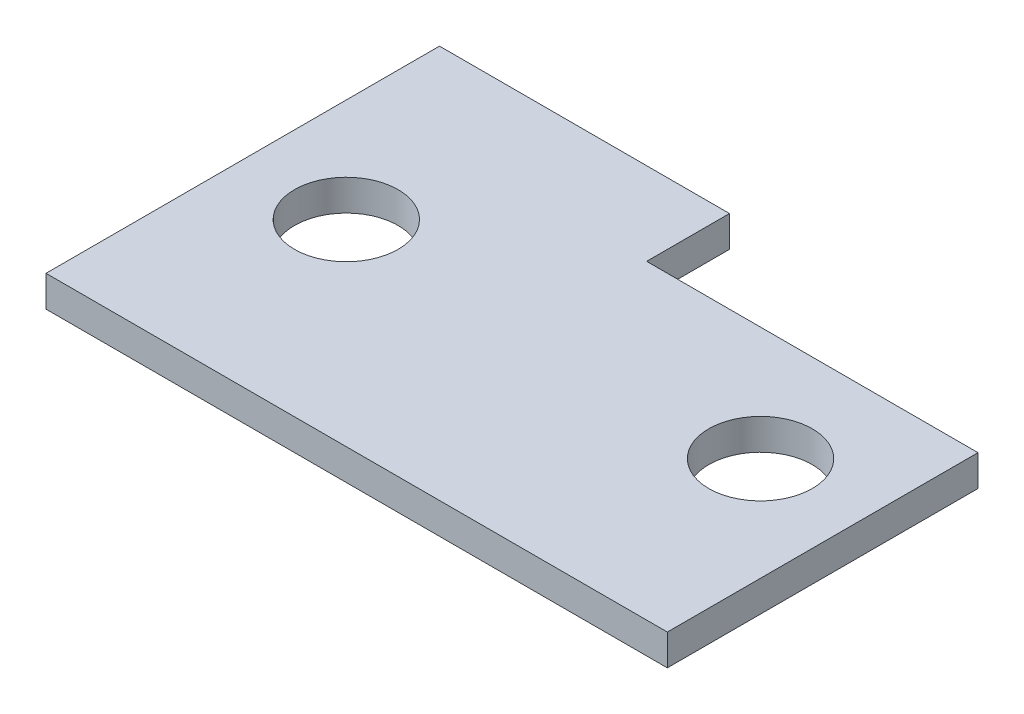
SolidWorks part; units mm, degrees
material "AISI 1020"
ref_plane "Спереди" through (0, 0, 0) normal (0, 0, 1) x (1, 0, 0)
ref_plane "Сверху" through (0, 0, 0) normal (0, 1, 0) x (1, 0, 0)
ref_plane "Справа" through (0, 0, 0) normal (1, 0, 0) x (0, 0, -1)
sketch "Эскиз1" plane through (0, 0, 0) normal (1, 0, 0) x (0, 0, -1)
  line L0 (-2, 7.746) -> (-2, 10.746) construction
  line L1 (-2, 7.746) -> (-40, 7.746) construction
  line L2 (-40, 7.746) -> (-40, 10.746) construction
  line L3 (-2, 10.746) -> (-40, 10.746) construction
  line L4 (-2, 7.746) -> (-2, 10.746)
  line L5 (-2, 7.746) -> (-40, 7.746)
  line L6 (-40, 7.746) -> (-40, 10.746)
  line L7 (-2, 10.746) -> (-40, 10.746)
extrude "Бобышка-Вытянуть1" add sketch "Эскиз1" along normal up to surface (30 mm away) and the other way up to surface (30 mm away)
sketch "Эскиз2" plane through (0, 10.746, 0) normal (0, 1, 0) x (1, 0, 0)
  line L0 (0, -8) -> (30, -8) construction
  line L1 (30, -2) -> (-2, -2)
  line L2 (30, -2) -> (30, -10)
  line L3 (30, -10) -> (-2, -10)
  line L4 (-2, -2) -> (-2, -10)
  line L5 (0, -2) -> (0, -40) construction
  line L6 (-20, -21) -> (20, -21) construction
  line L7 (0, -2) -> (0, -40) construction
  line L8 (-30, -40) -> (-30, -2) construction
  circle A0 centre (-20, -21) radius 5
  circle A1 centre (20, -21) radius 5
  point P11 (0, -21)
  point P14 (0, -21)
  dimension "D4" = 10
  dimension "D1" = 2
  dimension "D2" = 2
  dimension "D3" = 10
extrude "Вырез-Вытянуть1" cut sketch "Эскиз2" against normal through all
